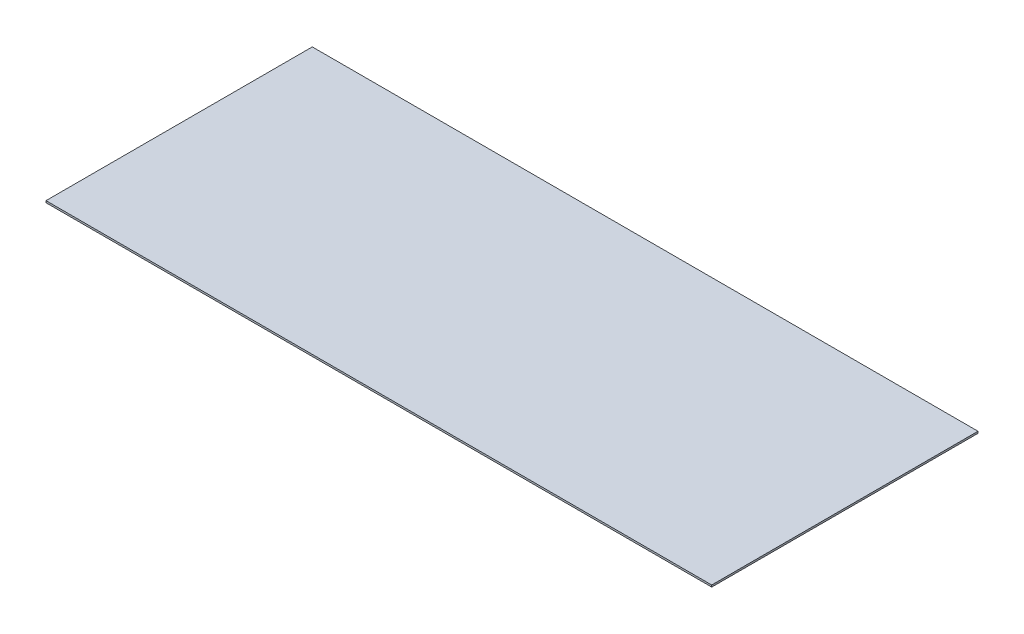
SolidWorks part; units mm, degrees
ref_plane "Front Plane" through (0, 0, 0) normal (0, 0, 1) x (1, 0, 0)
ref_plane "Top Plane" through (0, 0, 0) normal (0, 1, 0) x (1, 0, 0)
ref_plane "Right Plane" through (0, 0, 0) normal (1, 0, 0) x (0, 0, -1)
sketch "Sketch1" plane through (0, 0, 0) normal (0, 1, 0) x (1, 0, 0)
  line L1 (0, 0) -> (2286, 0)
  line L2 (0, 0) -> (0, 914.4)
  line L3 (0, 914.4) -> (2286, 914.4)
  line L4 (2286, 0) -> (2286, 914.4)
  dimension "D1" = 914.4
  dimension "D2" = 2286
extrude "Boss-Extrude1" add sketch "Sketch1" along normal blind 6.35
